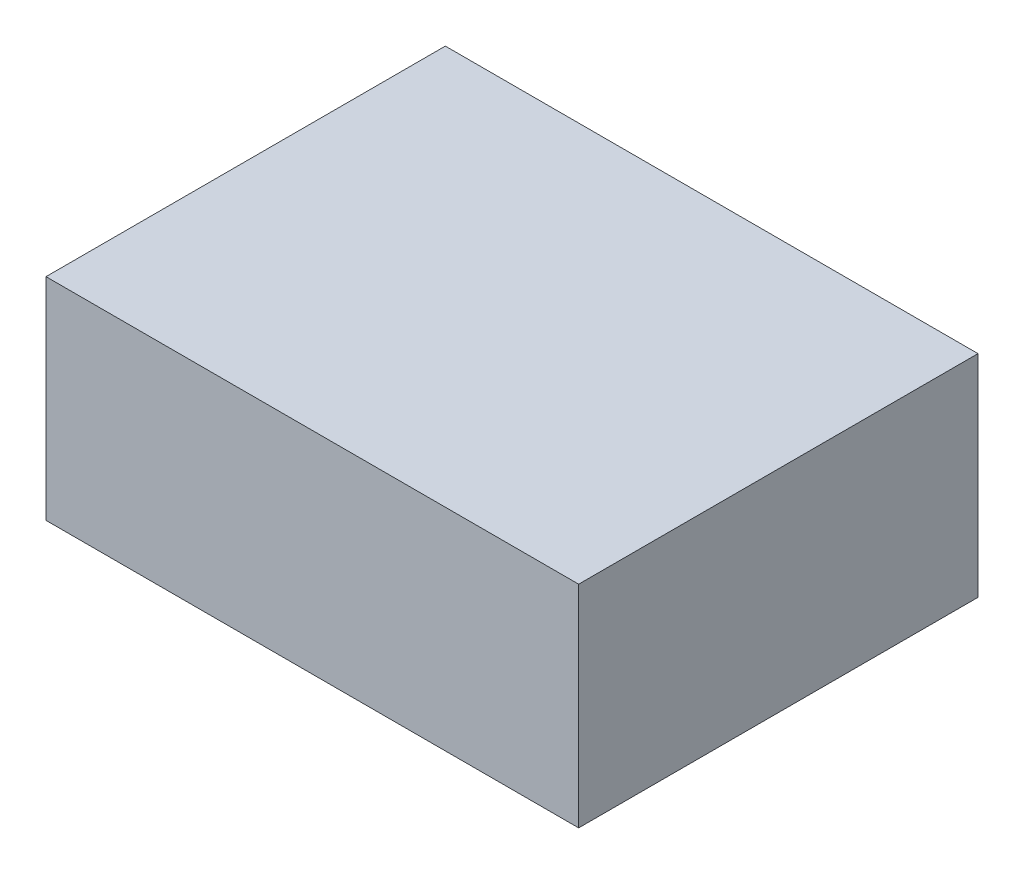
SolidWorks part; units mm, degrees
ref_plane "Front Plane" through (0, 0, 0) normal (0, 0, 1) x (1, 0, 0)
ref_plane "Top Plane" through (0, 0, 0) normal (0, 1, 0) x (1, 0, 0)
ref_plane "Right Plane" through (0, 0, 0) normal (1, 0, 0) x (0, 0, -1)
sketch "Sketch1" plane through (0, 0, 0) normal (0, 1, 0) x (1, 0, 0)
  line L1 (-4.315, 3.235) -> (4.315, 3.235)
  line L2 (-4.315, 3.235) -> (-4.315, -3.235)
  line L3 (-4.315, -3.235) -> (4.315, -3.235)
  line L4 (4.315, 3.235) -> (4.315, -3.235)
  line L5 (-4.315, 3.235) -> (4.315, -3.235) construction
  line L6 (-4.315, -3.235) -> (4.315, 3.235) construction
  point P0 (0, 0)
  dimension "D1" = 8.63
  dimension "D2" = 6.47
extrude "Boss-Extrude1" add sketch "Sketch1" along normal blind 3.42
